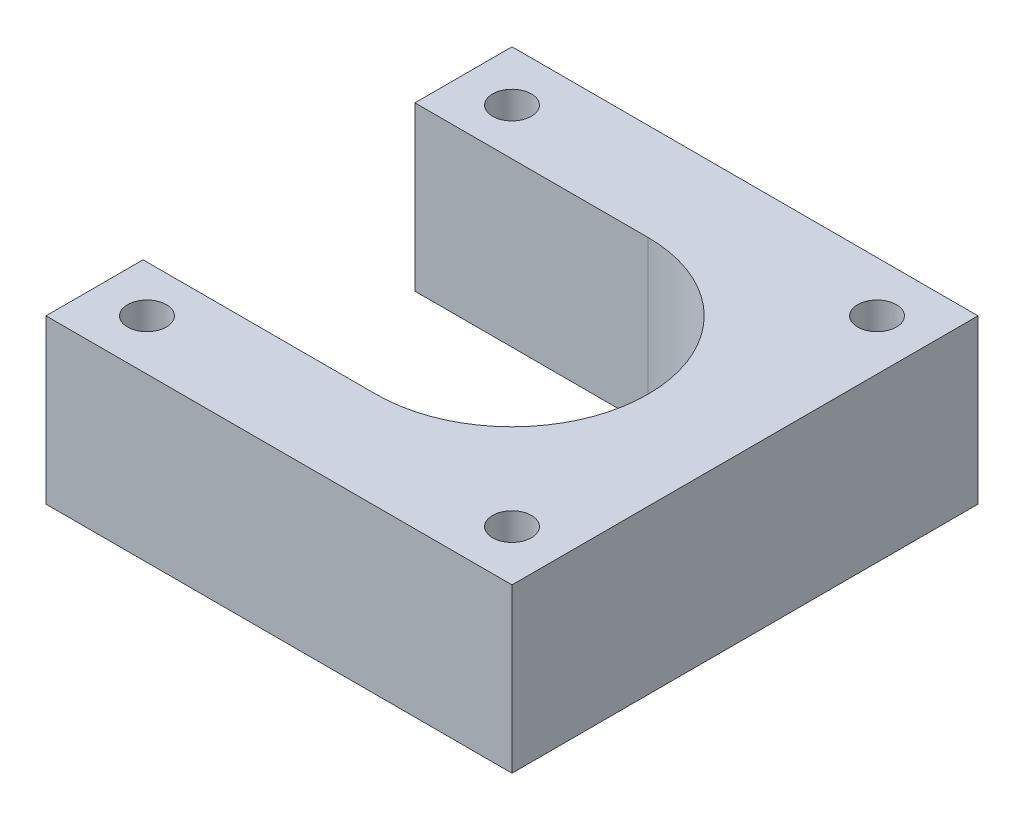
SolidWorks part; units mm, degrees
ref_plane "Front Plane" through (0, 0, 0) normal (0, 0, 1) x (1, 0, 0)
ref_plane "Top Plane" through (0, 0, 0) normal (0, 1, 0) x (1, 0, 0)
ref_plane "Right Plane" through (0, 0, 0) normal (1, 0, 0) x (0, 0, -1)
sketch "Sketch1" plane through (0, 0, 0) normal (0, 1, 0) x (1, 0, 0)
  line L0 (0, 17.5) -> (-30, 17.5)
  line L1 (-30, 30) -> (30, 30)
  line L2 (-30, 30) -> (-30, 17.5)
  line L3 (-30, -30) -> (30, -30)
  line L4 (30, 30) -> (30, -30)
  line L5 (-30, 30) -> (30, -30) construction
  line L6 (-30, -30) -> (30, 30) construction
  line L7 (0, -17.5) -> (-30, -17.5)
  line L8 (-30, -17.5) -> (-30, -30)
  circle A0 centre (-23.5, 23.5) radius 2.5
  circle A1 centre (23.5, 23.5) radius 2.5
  circle A2 centre (-23.5, -23.5) radius 2.5
  circle A3 centre (23.5, -23.5) radius 2.5
  arc A4 (0, -17.5) -> (0, 17.5) centre (0, 0) ccw
  point P0 (0, 0)
  dimension "D3" = 5
  dimension "D8" = 35
  dimension "D1" = 60
  dimension "D2" = 60
  dimension "D4" = 47
  dimension "D5" = 47
  dimension "D6" = 23.5
  dimension "D7" = 23.5
extrude "Boss-Extrude1" add sketch "Sketch1" along normal blind 21
